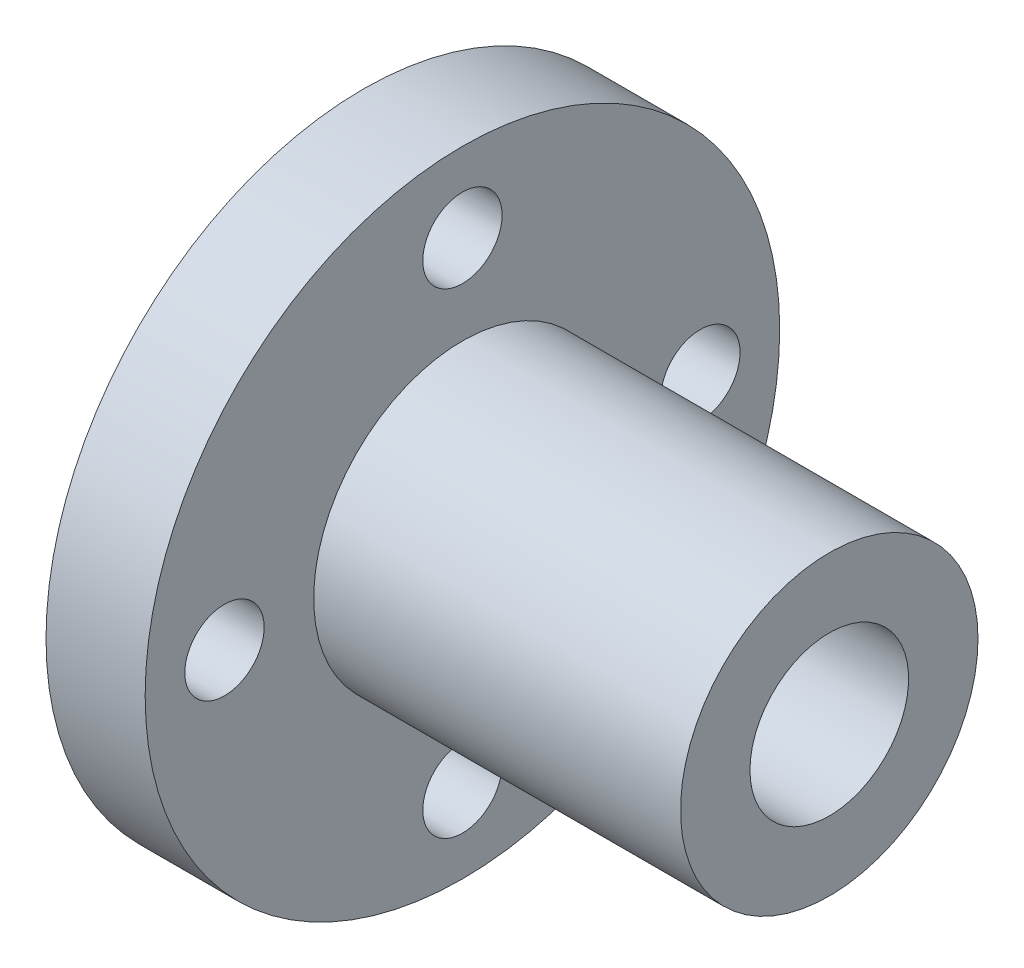
SolidWorks part; units mm, degrees
ref_plane "Front Plane" through (0, 0, 0) normal (0, 0, 1) x (1, 0, 0)
ref_plane "Top Plane" through (0, 0, 0) normal (0, 1, 0) x (1, 0, 0)
ref_plane "Right Plane" through (0, 0, 0) normal (1, 0, 0) x (0, 0, -1)
sketch "Sketch1" plane through (0, 0, 0) normal (1, 0, 0) x (0, 0, -1)
  circle A0 centre (0, 0) radius 16
  circle A1 centre (0, 12) radius 2
  circle A2 centre (12, 0) radius 2
  circle A3 centre (0, -12) radius 2
  circle A4 centre (-12, 0) radius 2
  point P14 (0, 0)
  dimension "D1" = 32
  dimension "D2" = 4
  dimension "D3" = 12
  dimension "D4" = 4
extrude "Boss-Extrude1" add sketch "Sketch1" along normal blind 5
sketch "Sketch2" plane through (5, 0, 0) normal (1, 0, 0) x (0, 0, -1)
  circle A0 centre (0, 0) radius 7.5
  dimension "D1" = 15
extrude "Boss-Extrude2" add sketch "Sketch2" along normal blind 18.5
sketch "Sketch3" plane through (0, 0, 0) normal (-1, 0, 0) x (0, 0, 1)
  circle A0 centre (0, 0) radius 4
  dimension "D1" = 8
extrude "Cut-Extrude1" cut sketch "Sketch3" against normal through all both and the other way through all
